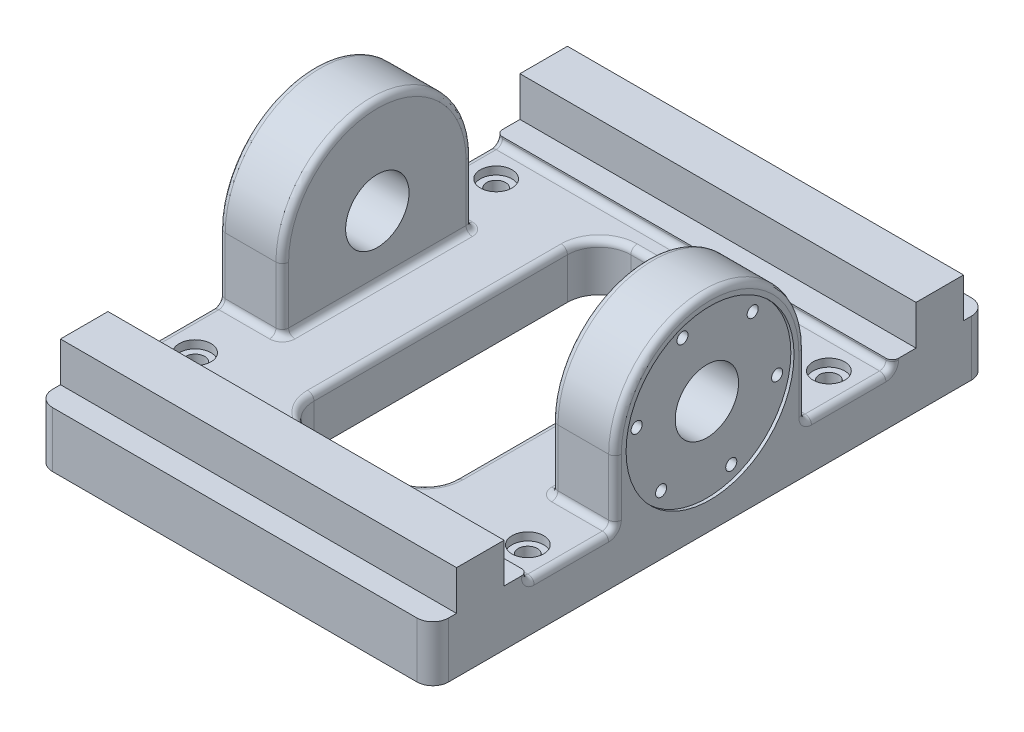
SolidWorks part; units mm, degrees
ref_plane "Front" through (0, 0, 0) normal (0, 0, 1) x (1, 0, 0)
ref_plane "Top" through (0, 0, 0) normal (0, 1, 0) x (1, 0, 0)
ref_plane "Right" through (0, 0, 0) normal (1, 0, 0) x (0, 0, -1)
sketch "Sketch1" plane through (0, 0, 0) normal (0, 1, 0) x (1, 0, 0)
  line L1 (-125, 175) -> (125, 175)
  line L2 (-125, 175) -> (-125, -175)
  line L3 (-125, -175) -> (125, -175)
  line L4 (125, 175) -> (125, -175)
  point P4 (-125, 0)
  point P5 (0, 175)
  dimension "D1" = 250
  dimension "D2" = 350
extrude "Extrude1" add sketch "Sketch1" along normal blind 30
sketch "Sketch26" [suppressed] plane through (0, 0, 0) normal (0, 0, 1) x (1, 0, 0)
  line L1 (-75, 10) -> (75, 10)
  line L2 (-75, 10) -> (-75, 0)
  line L3 (-75, 0) -> (75, 0)
  line L4 (75, 10) -> (75, 0)
  line L5 (-125, 0) -> (125, 0) construction
  point P6 (0, 0)
  dimension "D1" = 10
  dimension "D2" = 150
extrude "Cut-Extrude13" [suppressed] cut sketch "Sketch26" against normal through all and the other way through all
sketch "Sketch21" plane through (0, 30, 0) normal (0, 1, 0) x (-1, 0, 0)
  line L1 (-25, -100) -> (25, -100)
  line L2 (-45, -80) -> (-45, 80)
  line L3 (-25, 100) -> (25, 100)
  line L4 (45, -80) -> (45, 80)
  arc A0 (-25, -100) -> (-45, -80) centre (-25, -80) cw
  arc A1 (45, -80) -> (25, -100) centre (25, -80) cw
  arc A2 (25, 100) -> (45, 80) centre (25, 80) cw
  arc A3 (-25, 100) -> (-45, 80) centre (-25, 80) ccw
  point P4 (0, 100)
  point P7 (-45, -100)
  point P14 (-45, 100)
  point P15 (-45, 0)
  dimension "D3" = 20
  dimension "D2" = 200
  dimension "D4" = 90
extrude "Cut-Extrude10" cut sketch "Sketch21" against normal blind 100
sketch "Sketch2" plane through (0, 30, 0) normal (0, 1, 0) x (-1, 0, 0)
  line L0 (-125, 175) -> (-125, -175) construction
  line L1 (125, 130) -> (-125, 130)
  line L2 (125, 130) -> (125, 160)
  line L3 (125, 160) -> (-125, 160)
  line L4 (-125, 130) -> (-125, 160)
  line L5 (125, -175) -> (125, 175) construction
  line L7 (125, 175) -> (-125, 175) construction
  dimension "D1" = 30
  dimension "D2" = 15
extrude "Extrude2" add sketch "Sketch2" along normal blind 30
sketch "Sketch7" plane through (0, 30, 0) normal (0, 1, 0) x (-1, 0, 0)
  line L0 (125, 175) -> (-125, 175) construction
  line L1 (125, 115) -> (-125, 115)
  line L2 (125, 115) -> (125, 175)
  line L3 (125, 175) -> (-125, 175)
  line L4 (-125, 115) -> (-125, 175)
  line L5 (-125, 130) -> (-125, -175) construction
  line L6 (125, -175) -> (125, 130) construction
  dimension "D1" = 60
extrude "Extrude6" add sketch "Sketch7" along normal blind 5
mirror "Mirror1" about plane through (0, 0, 0) normal (0, 0, 1) of "Extrude6", "Extrude2"
sketch "Sketch3" plane through (-125, 0, 0) normal (1, 0, 0) x (0, 0, -1)
  line L0 (175, 35) -> (175, 0) construction
  line L1 (-115, 30) -> (115, 30) construction
  line L2 (-60, 70) -> (-60, 30)
  line L3 (60, 70) -> (60, 30)
  line L4 (-60, 30) -> (60, 30)
  arc A0 (60, 70) -> (-60, 70) centre (0, 70) ccw
  dimension "D1" = 120
  dimension "D3" = 40
extrude "Extrude3" add sketch "Sketch3" along normal blind 40
sketch "Sketch11" plane through (-125, 0, 0) normal (-1, 0, 0) x (0, 0, 1)
  circle A0 centre (0, 70) radius 53
  arc A1 (60, 70) -> (-60, 70) centre (0, 70) ccw construction
  dimension "D1" = 106
extrude "Cut-Extrude7" cut sketch "Sketch11" against normal blind 2
sketch "Sketch10" plane through (-125, 0, 0) normal (-1, 0, 0) x (0, 0, 1)
  line L0 (0, 70) -> (15.3909, 112.2862) construction
  line L1 (0, 70) -> (-12.7333, 70) construction
  circle A0 centre (15.3909, 112.2862) radius 3.5
  circle A1 centre (0, 70) radius 45 construction
  arc A2 (60, 70) -> (-60, 70) centre (0, 70) ccw construction
  dimension "D1" = 90
  dimension "D2" = 7
  dimension "D3" = 70
extrude "Cut-Extrude6" cut sketch "Sketch10" against normal blind 30
pattern_circular "CirPattern1" count 6 over 360 about axis through (0, 70, 0) along (1, 0, 0) of "Cut-Extrude6"
mirror "Mirror2" about plane through (0, 0, 0) normal (1, 0, 0) of "Extrude3", "Cut-Extrude7", "Cut-Extrude6", "CirPattern1"
sketch "Sketch6" plane through (0, 0, 0) normal (1, 0, 0) x (0, 0, -1)
  circle A0 centre (0, 70) radius 20
  arc A1 (60, 70) -> (-60, 70) centre (0, 70) ccw construction
  dimension "D1" = 40
extrude "Cut-Extrude1" cut sketch "Sketch6" against normal through all and the other way through all
hole_wizard "Hole2" positions "Sketch19" profile "Sketch18" legacy end condition through all
sketch "Sketch19" plane through (0, 30, 0) normal (0, 1, 0) x (-1, 0, 0)
  line L1 (-125, 175) -> (-125, -175) construction
  line L2 (-125, -175) -> (125, -175) construction
  point P0 (-105, -95)
  dimension "D1" = 80
  dimension "D2" = 20
sketch "Sketch18" plane through (105, 30, -95) normal (1, 0, 0) x (0, 0, 1)
  line L0 (0, 0) -> (0, 30)
  line L1 (0, 30) -> (6, 30)
  line L2 (6, 30) -> (6, 5)
  line L3 (6, 5) -> (10, 5)
  line L4 (10, 5) -> (10, 0)
  line L5 (10, 0) -> (0, 0)
  line L6 (0, 110) -> (0, -10) construction
  dimension "Diameter" = 12
  dimension "Depth" = 30
  dimension "C-Bore Diameter" = 20
  dimension "C-Bore Depth" = 5
pattern_linear "LPattern1" count 2 spacing 190 along (0, 0, 1) count 2 spacing 210 along (-1, 0, 0) of "Hole2"
fillet "Fillet1" radius 4 36 edges at (-125, 32.5, 115) (-125, 50, 60) (-85, 50, 60) (-125, 130, 0) (-85, 130, 0) (-125, 50, -60) (-85, 50, -60) (105, 30, -60) (-105, 30, -60) (85, 30, 0) (-85, 30, 0) (125, 32.5, 115) (125, 32.5, -115) (-125, 32.5, -115) (-39.1421, 30, -94.1421) (0, 30, -100) (39.1421, 30, -94.1421) (45, 30, 0) (39.1421, 30, 94.1421) (0, 30, 100) (-39.1421, 30, 94.1421) (85, 50, -60) (85, 50, 60) (125, 50, 60) (125, 130, 0) (85, 130, 0) (0, 30, 115) (-45, 30, 0) (105, 30, 60) (125, 50, -60) (0, 30, -115) (-105, 30, 60)
fillet "Fillet2" radius 10 4 edges at (-125, 17.5, 175) (125, 17.5, 175) (-125, 17.5, -175) (125, 17.5, -175)
